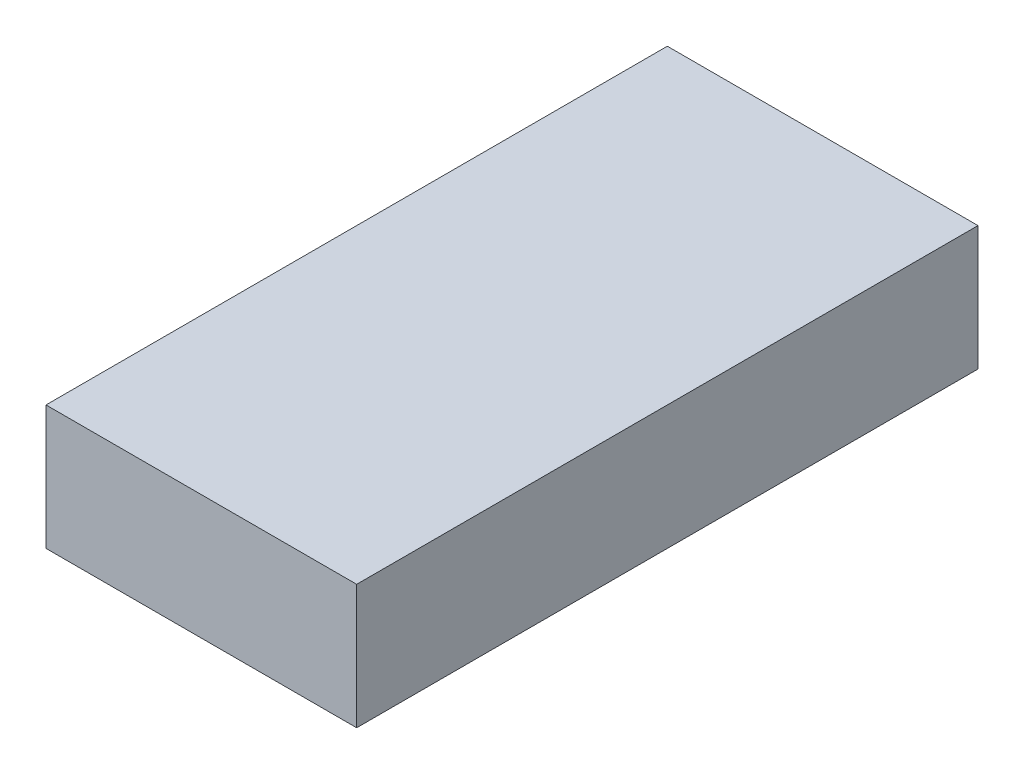
SolidWorks part; units mm, degrees
ref_plane "前视基准面" through (0, 0, 0) normal (0, 0, 1) x (1, 0, 0)
ref_plane "上视基准面" through (0, 0, 0) normal (0, 1, 0) x (1, 0, 0)
ref_plane "右视基准面" through (0, 0, 0) normal (1, 0, 0) x (0, 0, -1)
sketch "草图1" plane through (0, 0, 0) normal (0, 1, 0) x (1, 0, 0)
  line L1 (12.5, -25) -> (-12.5, -25)
  line L2 (12.5, -25) -> (12.5, 25)
  line L3 (12.5, 25) -> (-12.5, 25)
  line L4 (-12.5, -25) -> (-12.5, 25)
  line L5 (12.5, -25) -> (-12.5, 25) construction
  line L6 (12.5, 25) -> (-12.5, -25) construction
  point P0 (0, 0)
extrude "凸台-拉伸1" add sketch "草图1" along normal blind 10
